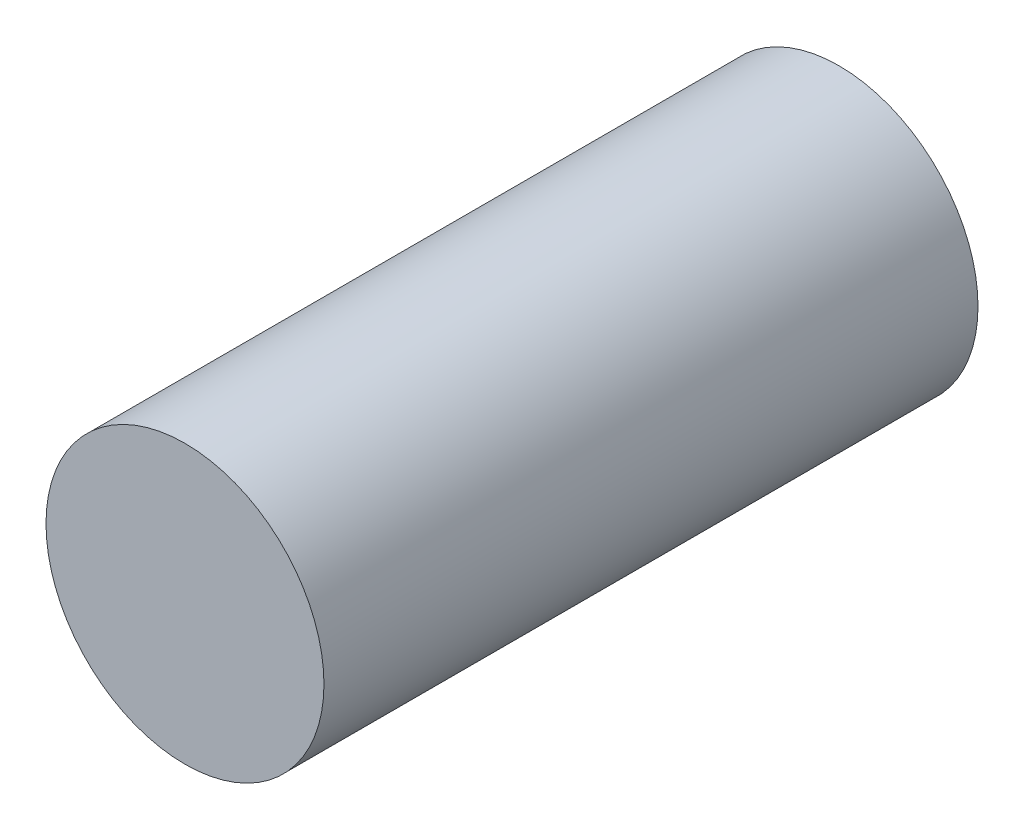
SolidWorks part; units mm, degrees
ref_plane "Front Plane" through (0, 0, 0) normal (0, 0, 1) x (1, 0, 0)
ref_plane "Top Plane" through (0, 0, 0) normal (0, 1, 0) x (1, 0, 0)
ref_plane "Right Plane" through (0, 0, 0) normal (1, 0, 0) x (0, 0, -1)
sketch "Sketch1" plane through (0, 0, 0) normal (0, 0, 1) x (1, 0, 0)
  circle A0 centre (-56.3489, 15.3746) radius 1.7
extrude "Boss-Extrude1" add sketch "Sketch1" along normal blind 7 and the other way up to surface (1 mm away)
